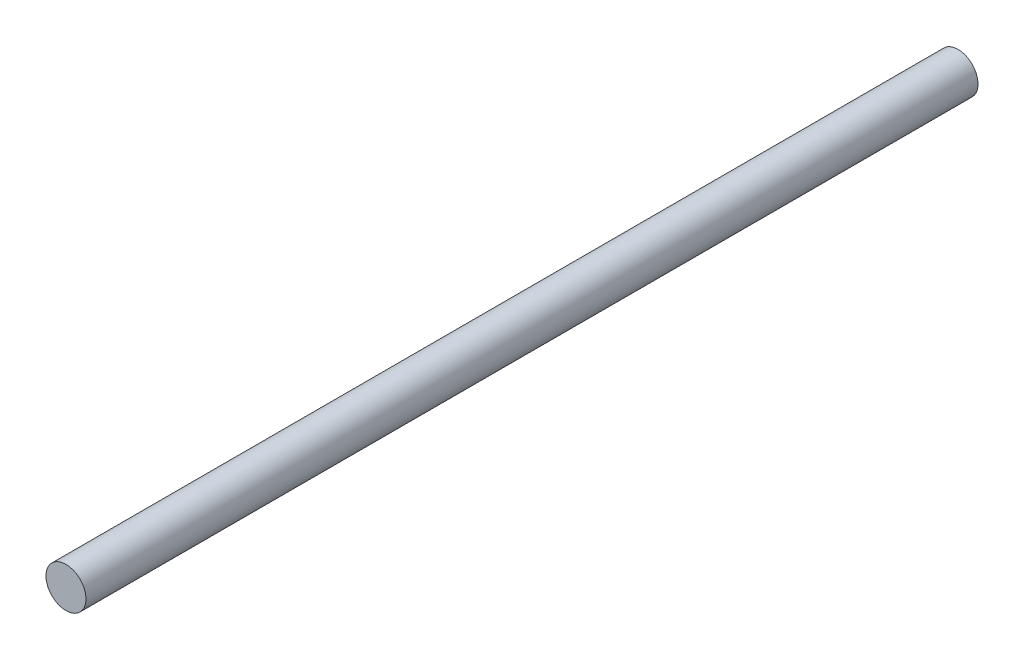
SolidWorks part; units mm, degrees
ref_plane "Front Plane" through (0, 0, 0) normal (0, 0, 1) x (1, 0, 0)
ref_plane "Top Plane" through (0, 0, 0) normal (0, 1, 0) x (1, 0, 0)
ref_plane "Right Plane" through (0, 0, 0) normal (1, 0, 0) x (0, 0, -1)
sketch "Sketch1" plane through (0, 0, 0) normal (0, 0, 1) x (1, 0, 0)
  circle A0 centre (0, 0) radius 3.365
  dimension "D1" = 6.73
extrude "Boss-Extrude1" add sketch "Sketch1" along normal blind 150
